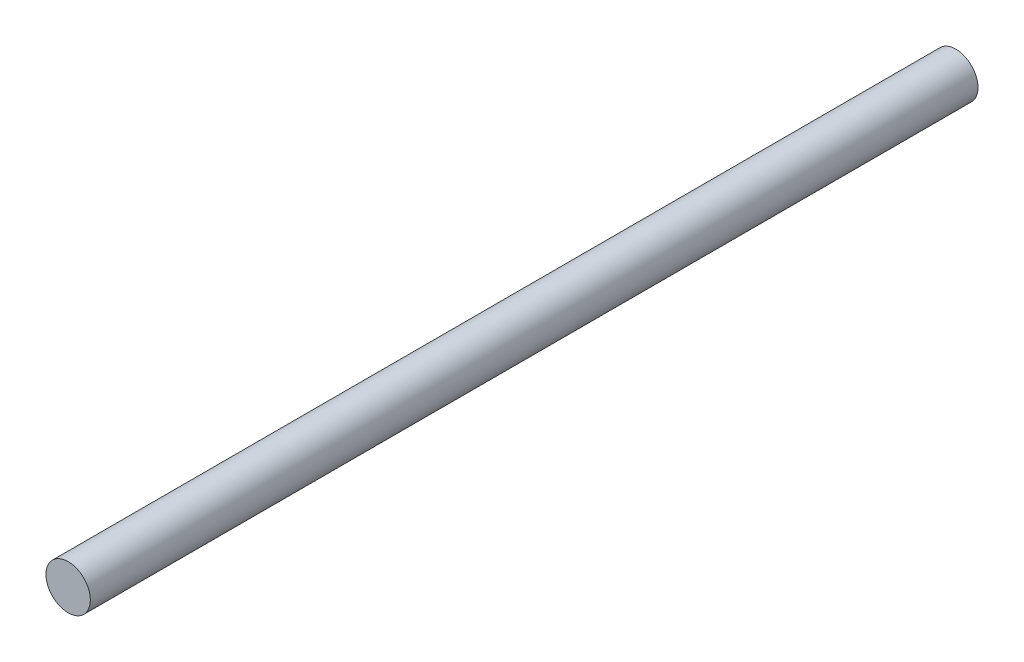
SolidWorks part; units mm, degrees
ref_plane "Front Plane" through (0, 0, 0) normal (0, 0, 1) x (1, 0, 0)
ref_plane "Top Plane" through (0, 0, 0) normal (0, 1, 0) x (1, 0, 0)
ref_plane "Right Plane" through (0, 0, 0) normal (1, 0, 0) x (0, 0, -1)
sketch "Sketch1" plane through (0, 0, 0) normal (0, 0, 1) x (1, 0, 0)
  circle A0 centre (0, 0) radius 3.175
  dimension "D1" = 6.35
extrude "Boss-Extrude1" add sketch "Sketch1" against normal blind 127
